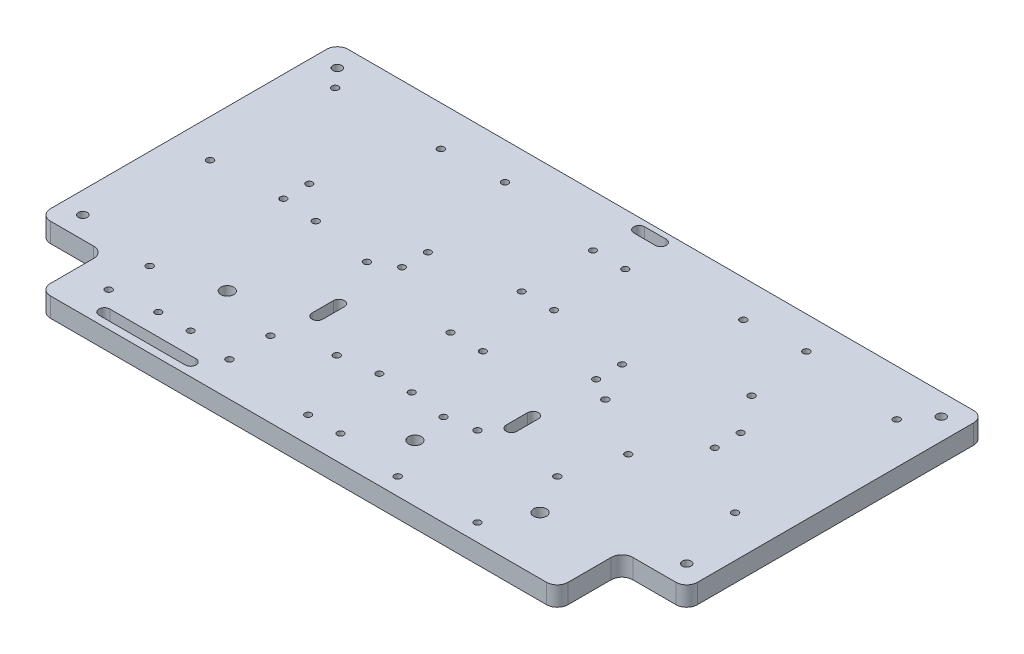
SolidWorks part; units mm, degrees
ref_plane "Plan de face" through (0, 0, 0) normal (0, 0, 1) x (1, 0, 0)
ref_plane "Plan de dessus" through (0, 0, 0) normal (0, 1, 0) x (1, 0, 0)
ref_plane "Plan de droite" through (0, 0, 0) normal (1, 0, 0) x (0, 0, -1)
sketch "Esquisse1" plane through (0, 0, 0) normal (0, 1, 0) x (1, 0, 0)
  line L0 (0, 81.3484) -> (0, -60.6791) construction
  line L1 (-137.8937, 0) -> (185.4331, 0) construction
  line L4 (150, -69) -> (150, 69)
  line L6 (-150, -69) -> (-150, 69)
  line L7 (150, -69) -> (-150, 69) construction
  line L8 (150, 69) -> (-150, -69) construction
  line L13 (80, -48.6) -> (80, 59) construction
  line L18 (-149.8488, 69) -> (-150, 69)
  line L22 (80, 59) -> (133.34, 59) construction
  line L23 (133.34, 59) -> (133.34, -48.6) construction
  line L24 (-104, -64) -> (-48, -64) construction
  line L25 (-104, -64) -> (-104, -83) construction
  line L26 (-104, -83) -> (-48, -83) construction
  line L27 (-48, -64) -> (-48, -83) construction
  line L28 (-104, -64) -> (-48, -83) construction
  line L29 (-104, -83) -> (-48, -64) construction
  line L35 (-132.5, 50.5) -> (-83.5, 50.5) construction
  line L40 (-76, -86) -> (-76, -93) construction
  line L46 (-56, -93) -> (-96, -93) construction
  line L47 (-56, -95.5) -> (-96, -95.5)
  line L53 (133.34, -48.6) -> (80, -48.6) construction
  line L54 (-136, 54) -> (-80, 54) construction
  line L55 (-136, 54) -> (-136, -34) construction
  line L56 (-136, -34) -> (-80, -34) construction
  line L57 (-80, 54) -> (-80, -34) construction
  line L58 (-136, 54) -> (-80, -34) construction
  line L59 (-136, -34) -> (-80, 54) construction
  line L60 (-107, -61) -> (-45, -61) construction
  line L61 (-107, -61) -> (-107, -86) construction
  line L62 (-107, -86) -> (-45, -86) construction
  line L63 (-45, -61) -> (-45, -86) construction
  line L64 (-107, -61) -> (-45, -86) construction
  line L65 (-107, -86) -> (-45, -61) construction
  line L66 (82.54, -48.6) -> (82.54, 59) construction
  line L67 (130.8, -48.6) -> (130.8, 59) construction
  line L68 (80, -42.6) -> (133.34, -42.6) construction
  line L69 (87.62, 23.44) -> (87.62, 59) construction
  line L71 (-120, -99) -> (120, -99)
  line L72 (120, -99) -> (120, -69)
  line L73 (-149.8488, 69) -> (150, 69)
  line L75 (120, -69) -> (150, -69)
  line L76 (-150, -69) -> (150, -69) construction
  line L77 (-150, -69) -> (-120, -69)
  line L78 (-120, -69) -> (-120, -99)
  line L79 (-63.25, 59) -> (-63.25, -19) construction
  line L80 (-63.25, -19) -> (-29.75, -19) construction
  line L81 (-29.75, -19) -> (-29.75, -61.5) construction
  line L82 (-29.75, -61.5) -> (29.75, -61.5) construction
  line L83 (29.75, -61.5) -> (29.75, -19) construction
  line L84 (29.75, -19) -> (63.25, -19) construction
  line L85 (63.25, -19) -> (63.25, 59) construction
  line L86 (63.25, 59) -> (-63.25, 59) construction
  line L87 (-83.5, 50.5) -> (-83.5, -7.5) construction
  line L88 (38, -54) -> (75, -54) construction
  line L89 (38, -54) -> (38, -91) construction
  line L90 (38, -91) -> (75, -91) construction
  line L91 (75, -54) -> (75, -91) construction
  line L92 (38, -54) -> (75, -91) construction
  line L93 (38, -91) -> (75, -54) construction
  line L94 (35, -51) -> (78, -51) construction
  line L95 (35, -51) -> (35, -94) construction
  line L96 (35, -94) -> (78, -94) construction
  line L97 (78, -51) -> (78, -94) construction
  line L98 (35, -51) -> (78, -94) construction
  line L99 (35, -94) -> (78, -51) construction
  line L100 (-83.5, -7.5) -> (-132.5, -7.5) construction
  line L101 (-132.5, -7.5) -> (-132.5, 50.5) construction
  line L102 (-108, 54) -> (-108, -34) construction
  line L103 (0, -61.5) -> (0, 59) construction
  line L104 (-63.25, 20) -> (63.25, 20) construction
  line L105 (-55.25, 52) -> (55.25, 52) construction
  line L106 (-55.25, 52) -> (-55.25, -12) construction
  line L107 (-55.25, -12) -> (55.25, -12) construction
  line L108 (55.25, 52) -> (55.25, -12) construction
  line L109 (-55.25, 52) -> (55.25, -12) construction
  line L110 (-55.25, -12) -> (55.25, 52) construction
  line L111 (-29.75, -56.5) -> (29.75, -56.5) construction
  line L112 (-56, -90.5) -> (-96, -90.5)
  line L113 (27.5, -72.5) -> (85.5, -72.5) construction
  line L114 (-5, 64) -> (5, 64) construction
  line L115 (-5, 66.5) -> (5, 66.5)
  line L116 (-5, 61.5) -> (5, 61.5)
  line L117 (-45, -40.25) -> (45, -40.25) construction
  line L118 (-45, -35.25) -> (-45, -45.25) construction
  line L119 (-42.5, -35.25) -> (-42.5, -45.25)
  line L120 (-47.5, -35.25) -> (-47.5, -45.25)
  line L121 (45, -35.25) -> (45, -45.25) construction
  line L122 (42.5, -35.25) -> (42.5, -45.25)
  line L123 (47.5, -35.25) -> (47.5, -45.25)
  line L124 (-76, -61) -> (-76, -56) construction
  circle A0 centre (-140, 59) radius 2.05
  circle A1 centre (140, 59) radius 2.05
  circle A2 centre (140, -59) radius 2.05
  circle A3 centre (-140, -59) radius 2.05
  circle A19 centre (-48, -83) radius 1.55
  circle A20 centre (-104, -83) radius 1.55
  circle A21 centre (-48, -64) radius 1.55
  circle A22 centre (-104, -64) radius 1.55
  circle A27 centre (82.54, -28.63) radius 1.55
  circle A28 centre (130.8, -27.36) radius 1.55
  circle A29 centre (130.8, 47.57) radius 1.55
  circle A30 centre (82.54, 53.92) radius 1.55
  circle A31 centre (87.62, 23.44) radius 1.55
  circle A32 centre (38, -54) radius 1.55
  circle A33 centre (75, -54) radius 1.55
  circle A34 centre (75, -91) radius 1.55
  circle A35 centre (38, -91) radius 1.55
  circle A36 centre (-132.5, 50.5) radius 1.55
  circle A37 centre (-132.5, -7.5) radius 1.55
  circle A38 centre (-83.5, -7.5) radius 1.55
  circle A39 centre (-83.5, 50.5) radius 1.55
  circle A40 centre (-55.25, 52) radius 1.55
  circle A41 centre (-55.25, -12) radius 1.55
  circle A42 centre (55.25, 52) radius 1.55
  circle A43 centre (55.25, -12) radius 1.55
  circle A44 centre (-24.75, -56.5) radius 1.55
  circle A45 centre (24.75, -56.5) radius 1.55
  arc A46 (-56, -95.5) -> (-56, -90.5) centre (-56, -93) ccw
  arc A47 (-96, -90.5) -> (-96, -95.5) centre (-96, -93) ccw
  circle A48 centre (27.5, -72.5) radius 3
  circle A49 centre (85.5, -72.5) radius 3
  arc A50 (-5, 66.5) -> (-5, 61.5) centre (-5, 64) ccw
  arc A51 (5, 61.5) -> (5, 66.5) centre (5, 64) ccw
  arc A52 (-42.5, -35.25) -> (-47.5, -35.25) centre (-45, -35.25) ccw
  arc A53 (-47.5, -45.25) -> (-42.5, -45.25) centre (-45, -45.25) ccw
  arc A54 (42.5, -35.25) -> (47.5, -35.25) centre (45, -35.25) cw
  arc A55 (47.5, -45.25) -> (42.5, -45.25) centre (45, -45.25) cw
  circle A56 centre (-76, -56) radius 3
  point P1 (0, 0)
  point P21 (-76, -73.5)
  point P35 (0, 100)
  point P45 (-76, -93)
  point P61 (-76, -73.5)
  point P95 (56.5, -72.5)
  point P102 (56.5, -72.5)
  point P111 (35, -72.5)
  point P114 (0, 20)
  point P131 (0, 64)
  point P140 (-45, -40.25)
  point P147 (45, -40.25)
  dimension "D5" = 4.1
  dimension "D6" = 130
  dimension "D7" = 138
  dimension "D8" = 140
  dimension "D11" = 10
  dimension "D9" = 10
  dimension "D13" = 7.5
  dimension "D19" = 50.8
  dimension "D20" = 3.1
  dimension "D25" = 7.62
  dimension "D41" = 3.1
  dimension "D48" = 3.1
  dimension "D59" = 3.1
  dimension "D60" = 49.5
  dimension "D62" = 6
  dimension "D69" = 6
  dimension "D4" = 150
  dimension "D10" = 5
  dimension "D12" = 40
  dimension "D14" = 6
  dimension "D15" = 10
  dimension "D16" = 101.6
  dimension "D17" = 53.34
  dimension "D18" = 2.54
  dimension "D21" = 96.52
  dimension "D22" = 90.17
  dimension "D23" = 13.97
  dimension "D24" = 15.24
  dimension "D26" = 66.04
  dimension "D27" = 3
  dimension "D28" = 3
  dimension "D29" = 25
  dimension "D30" = 62
  dimension "D31" = 10
  dimension "D32" = 30
  dimension "D33" = 30
  dimension "D34" = 45
  dimension "D35" = 80
  dimension "D36" = 7.5
  dimension "D37" = 43
  dimension "D38" = 43
  dimension "D39" = 3
  dimension "D40" = 3
  dimension "D42" = 35
  dimension "D43" = 120
  dimension "D44" = 88
  dimension "D45" = 56
  dimension "D46" = 3.5
  dimension "D47" = 58
  dimension "D49" = 49
  dimension "D50" = 3.5
  dimension "D51" = 15
  dimension "D52" = 80
  dimension "D53" = 126.5
  dimension "D54" = 59.5
  dimension "D55" = 78
  dimension "D56" = 42.5
  dimension "D57" = 64
  dimension "D58" = 110.5
  dimension "D61" = 44.5
  dimension "D63" = 5
  dimension "D64" = 5
  dimension "D65" = 10
  dimension "D66" = 10
  dimension "D67" = 5
  dimension "D68" = 45
  dimension "D70" = 5
  dimension "D71" = 21.25
extrude "Boss.-Extru.1" add sketch "Esquisse1" along normal blind 9
fillet "Congé2" radius 5 8 edges at (150, 4.5, -69) (-150, 4.5, -69) (-150, 4.5, 69) (150, 4.5, 69) (120, 4.5, 69) (120, 4.5, 99) (-120, 4.5, 69) (-120, 4.5, 99)
sketch "Esquisse2" plane through (0, 9, 0) normal (0, 1, 0) x (1, 0, 0)
  line L0 (0, 69) -> (0, -99) construction
  line L1 (-150, 0) -> (150, 0) construction
  line L2 (0, 46.3302) -> (0, 45) construction
  line L3 (0, 45) -> (-7.5, 45) construction
  line L4 (-76, -90.5) -> (-76, -75) construction
  line L5 (-56, -90.5) -> (-96, -90.5) construction
  line L8 (150, -64) -> (150, 64)
  line L9 (145, 69) -> (-145, 69)
  line L10 (-150, 64) -> (-150, -64)
  line L11 (-145, -69) -> (-125, -69)
  line L12 (-120, -74) -> (-120, -94)
  line L13 (-115, -99) -> (115, -99)
  line L14 (120, -94) -> (120, -74)
  line L15 (125, -69) -> (145, -69)
  line L16 (150, -64) -> (150, 64)
  line L17 (145, 69) -> (-145, 69)
  line L18 (-150, 64) -> (-150, -64)
  line L19 (-145, -69) -> (-125, -69)
  line L20 (-120, -74) -> (-120, -94)
  line L21 (-115, -99) -> (115, -99)
  line L22 (120, -94) -> (120, -74)
  line L23 (125, -69) -> (145, -69)
  circle A0 centre (-7.5, 45) radius 1.5
  circle A1 centre (7.5, 45) radius 1.5
  circle A2 centre (-7.5, 12) radius 1.5
  circle A3 centre (7.5, 12) radius 1.5
  circle A4 centre (-7.5, -21) radius 1.5
  circle A5 centre (7.5, -21) radius 1.5
  circle A6 centre (-7.5, -54) radius 1.5
  circle A7 centre (7.5, -54) radius 1.5
  arc A8 (150, 64) -> (145, 69) centre (145, 64) ccw
  arc A9 (-145, 69) -> (-150, 64) centre (-145, 64) ccw
  arc A10 (-150, -64) -> (-145, -69) centre (-145, -64) ccw
  arc A11 (-120, -74) -> (-125, -69) centre (-125, -74) ccw
  arc A12 (-120, -94) -> (-115, -99) centre (-115, -94) ccw
  arc A13 (115, -99) -> (120, -94) centre (115, -94) ccw
  arc A14 (125, -69) -> (120, -74) centre (125, -74) ccw
  arc A15 (145, -69) -> (150, -64) centre (145, -64) ccw
  arc A16 (150, 64) -> (145, 69) centre (145, 64) ccw
  arc A17 (-145, 69) -> (-150, 64) centre (-145, 64) ccw
  arc A18 (-150, -64) -> (-145, -69) centre (-145, -64) ccw
  arc A19 (-120, -74) -> (-125, -69) centre (-125, -74) ccw
  arc A20 (-120, -94) -> (-115, -99) centre (-115, -94) ccw
  arc A21 (115, -99) -> (120, -94) centre (115, -94) ccw
  arc A22 (125, -69) -> (120, -74) centre (125, -74) ccw
  arc A23 (145, -69) -> (150, -64) centre (145, -64) ccw
  circle A24 centre (-7.5, -87) radius 1.5
  circle A25 centre (7.5, -87) radius 1.5
  circle A26 centre (-100, 6) radius 1.5
  circle A27 centre (-100, -6) radius 1.5
  circle A28 centre (100, -6) radius 1.5
  circle A29 centre (100, 6) radius 1.5
  circle A30 centre (-83.5, -80.5) radius 1.5
  circle A31 centre (-68.5, -80.5) radius 1.5
  circle A32 centre (-45, -6) radius 1.5
  circle A33 centre (-45, 6) radius 1.5
  circle A34 centre (45, 6) radius 1.5
  circle A35 centre (45, -6) radius 1.5
  dimension "D2" = 3
  dimension "D6" = 6
  dimension "D7" = 3
  dimension "D10" = 7.5
  dimension "D11" = 3
  dimension "D3" = 7.5
  dimension "D4" = 45
  dimension "D8" = 100
  dimension "D9" = 33
  dimension "D12" = 10
  dimension "D14" = 55
  dimension "D1" = 0
  dimension "D5" = 5
  dimension "D13" = 2
  dimension "D15" = 2
extrude "Enlèv. mat.-Extru.1" cut sketch "Esquisse2" against normal blind 10 contours A0 | A1 | A3 | A2 | A4 | A5 | A6 | A7 | A24 | A25 | A27 | A26 | A28 | A29 | A31 | A30 | A32 | A33 | A35 | A34
